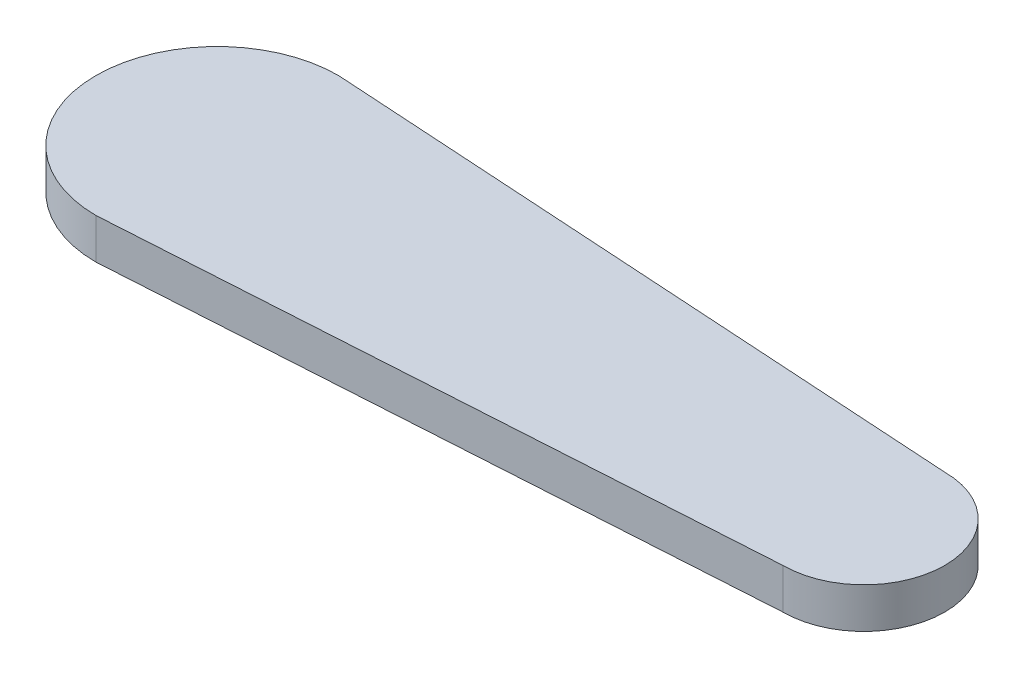
SolidWorks part; units mm, degrees
ref_plane "Front Plane" through (0, 0, 0) normal (0, 0, 1) x (1, 0, 0)
ref_plane "Top Plane" through (0, 0, 0) normal (0, 1, 0) x (1, 0, 0)
ref_plane "Right Plane" through (0, 0, 0) normal (1, 0, 0) x (0, 0, -1)
sketch "Sketch1" plane through (0, 0, 0) normal (0, 1, 0) x (1, 0, 0)
  line L0 (0, 15) -> (80, 10)
  line L1 (0, -15) -> (80, -10)
  arc A0 (0, 15) -> (0, -15) centre (0, 0) ccw
  arc A1 (80, -10) -> (80, 10) centre (80, 0) ccw
  dimension "D1" = 30
  dimension "D2" = 20
  dimension "D3" = 80
extrude "Boss-Extrude1" add sketch "Sketch1" along normal blind 5
